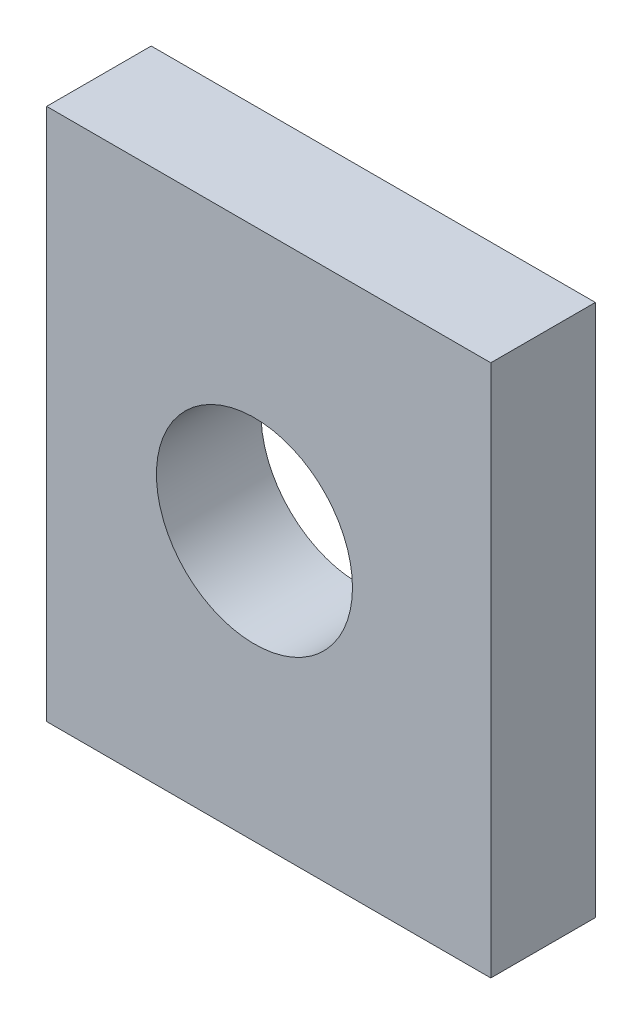
SolidWorks part; units mm, degrees
ref_plane "Front Plane" through (0, 0, 0) normal (0, 0, 1) x (1, 0, 0)
ref_plane "Top Plane" through (0, 0, 0) normal (0, 1, 0) x (1, 0, 0)
ref_plane "Right Plane" through (0, 0, 0) normal (1, 0, 0) x (0, 0, -1)
sketch "Sketch1" plane through (0, 0, 0) normal (0, 0, 1) x (1, 0, 0)
  line L1 (-8.325, 26.0121) -> (-18.52, 26.0121)
  line L2 (-8.325, 26.0121) -> (-8.325, 38.2421)
  line L3 (-8.325, 38.2421) -> (-18.52, 38.2421)
  line L4 (-18.52, 26.0121) -> (-18.52, 38.2421)
  point P0 (-13.425, 32.1271)
extrude "Boss-Extrude1" add sketch "Sketch1" against normal blind 2.4
sketch "Sketch4" plane through (0, 0, 0) normal (0, 0, 1) x (1, 0, 0)
  circle A0 centre (-13.75, 32.1871) radius 2.25
  dimension "D1" = 4.5
extrude "Cut-Extrude2" cut sketch "Sketch4" against normal blind 5
